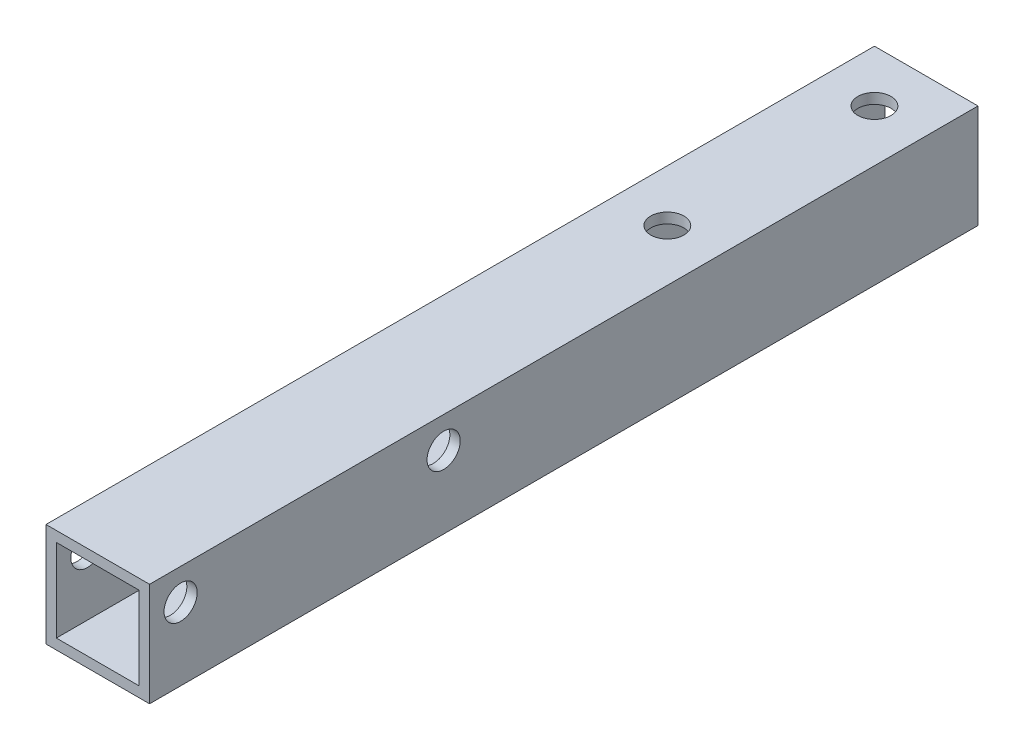
SolidWorks part; units mm, degrees
material "5052-H34"
ref_plane "正面" through (0, 0, 0) normal (0, 0, 1) x (1, 0, 0)
ref_plane "平面" through (0, 0, 0) normal (0, 1, 0) x (1, 0, 0)
ref_plane "右側面" through (0, 0, 0) normal (1, 0, 0) x (0, 0, -1)
sketch "ｽｹｯﾁ1" plane through (0, 0, 0) normal (0, 0, 1) x (1, 0, 0)
  line L1 (5, 5) -> (-5, 5)
  line L2 (5, 5) -> (5, -5)
  line L3 (5, -5) -> (-5, -5)
  line L4 (-5, 5) -> (-5, -5)
  line L5 (5, 5) -> (-5, -5) construction
  line L6 (5, -5) -> (-5, 5) construction
  point P0 (0, 0)
  dimension "D1" = 10
extrude "押し出し-薄板1" add sketch "ｽｹｯﾁ1" along normal blind 80 thin thin type one direction reverse wall 1
sketch "ｽｹｯﾁ2" plane through (0, 5, 0) normal (0, 1, 0) x (1, 0, 0)
  line L0 (0, 0) -> (0, -80) construction
  line L1 (5, 0) -> (-5, 0) construction
  line L2 (5, -80) -> (-5, -80) construction
  circle A0 centre (0, -5) radius 1.6
  circle A1 centre (0, -25) radius 1.6
  dimension "D1" = 3.2
  dimension "D2" = 5
  dimension "D3" = 20
extrude "ｶｯﾄ - 押し出し1" cut sketch "ｽｹｯﾁ2" against normal through all
sketch "ｽｹｯﾁ3" plane through (-5, 0, 0) normal (-1, 0, 0) x (0, 0, 1)
  line L0 (0, 2) -> (80, 2) construction
  line L1 (0, 5) -> (0, -5) construction
  line L2 (80, 5) -> (80, -5) construction
  line L3 (80, -5) -> (0, -5) construction
  circle A0 centre (77, 2) radius 1.6
  circle A1 centre (51.6, 2) radius 1.6
  dimension "D2" = 3
  dimension "D3" = 3.2
  dimension "D4" = 25.4
  dimension "D5" = 3.2
  dimension "D1" = 7
extrude "ｶｯﾄ - 押し出し2" cut sketch "ｽｹｯﾁ3" against normal through all
